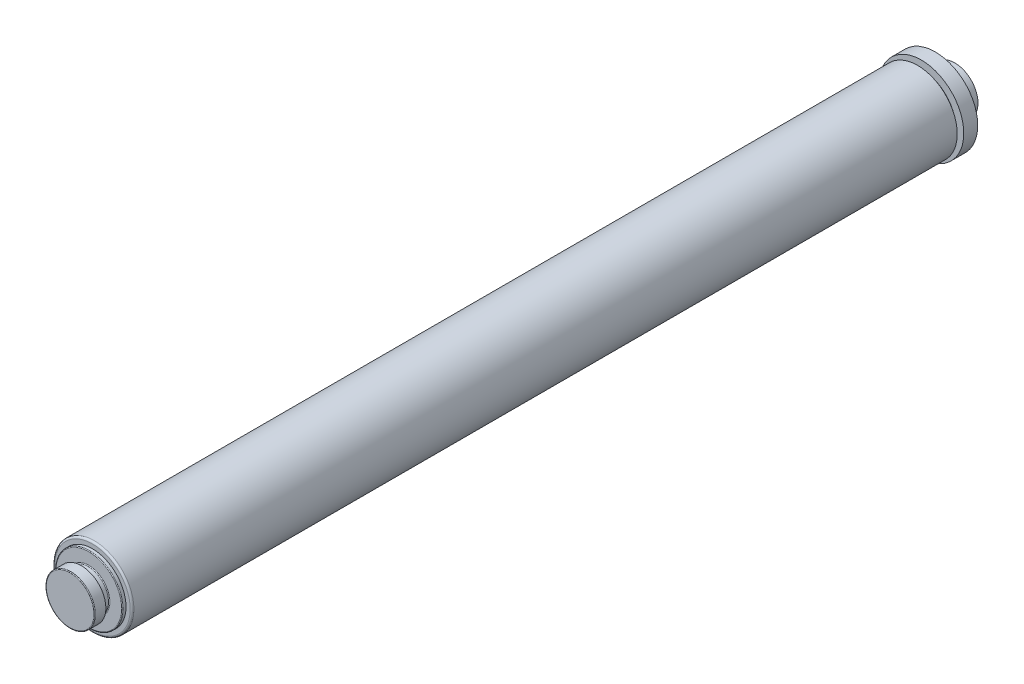
SolidWorks part; units mm, degrees
ref_plane "Front Plane" through (0, 0, 0) normal (0, 0, 1) x (1, 0, 0)
ref_plane "Top Plane" through (0, 0, 0) normal (0, 1, 0) x (1, 0, 0)
ref_plane "Right Plane" through (0, 0, 0) normal (1, 0, 0) x (0, 0, -1)
sketch "Sketch1" plane through (0, 0, 0) normal (0, 0, 1) x (1, 0, 0)
  circle A0 centre (0, 0) radius 26.9875
  dimension "D1" = 53.975
extrude "Boss-Extrude1" add sketch "Sketch1" along normal blind 562.356
sketch "Sketch2" plane through (0, 0, 562.356) normal (0, 0, 1) x (1, 0, 0)
  circle A0 centre (0, 0) radius 22.86
  dimension "D1" = 45.72
extrude "Boss-Extrude2" add sketch "Sketch2" along normal blind 2.54
sketch "Sketch3" plane through (0, 0, 564.896) normal (0, 0, 1) x (1, 0, 0)
  circle A0 centre (0, 0) radius 13.9158
  dimension "D1" = 27.8315
extrude "Boss-Extrude3" add sketch "Sketch3" along normal blind 5.08
sketch "Sketch4" plane through (0, 0, 569.976) normal (0, 0, 1) x (1, 0, 0)
  circle A0 centre (0, 0) radius 16.7318
  dimension "D1" = 33.4636
extrude "Boss-Extrude4" add sketch "Sketch4" along normal blind 7.62
fillet "Fillet1" radius 0.508 1 edges at (16.7318, 0, 577.596)
fillet "Fillet2" radius 0.508 1 edges at (13.9158, 0, 564.896)
fillet "Fillet3" radius 0.508 1 edges at (22.86, 0, 564.896)
fillet "Fillet4" radius 1.27 1 edges at (26.9875, 0, 562.356)
sketch "Sketch5" plane through (0, 0, 0) normal (0, 0, -1) x (-1, 0, 0)
  circle A0 centre (0, 0) radius 23.6278
  dimension "D1" = 47.2557
extrude "Boss-Extrude5" add sketch "Sketch5" along normal blind 2.54
sketch "Sketch6" plane through (0, 0, -2.54) normal (0, 0, -1) x (-1, 0, 0)
  circle A0 centre (0, 0) radius 28.8925
  dimension "D1" = 57.785
extrude "Boss-Extrude6" add sketch "Sketch6" along normal blind 9.525
sketch "Sketch7" plane through (0, 0, -12.065) normal (0, 0, -1) x (-1, 0, 0)
  circle A0 centre (0, 0) radius 15.875
  dimension "D1" = 31.75
extrude "Boss-Extrude7" add sketch "Sketch7" along normal blind 13.208
